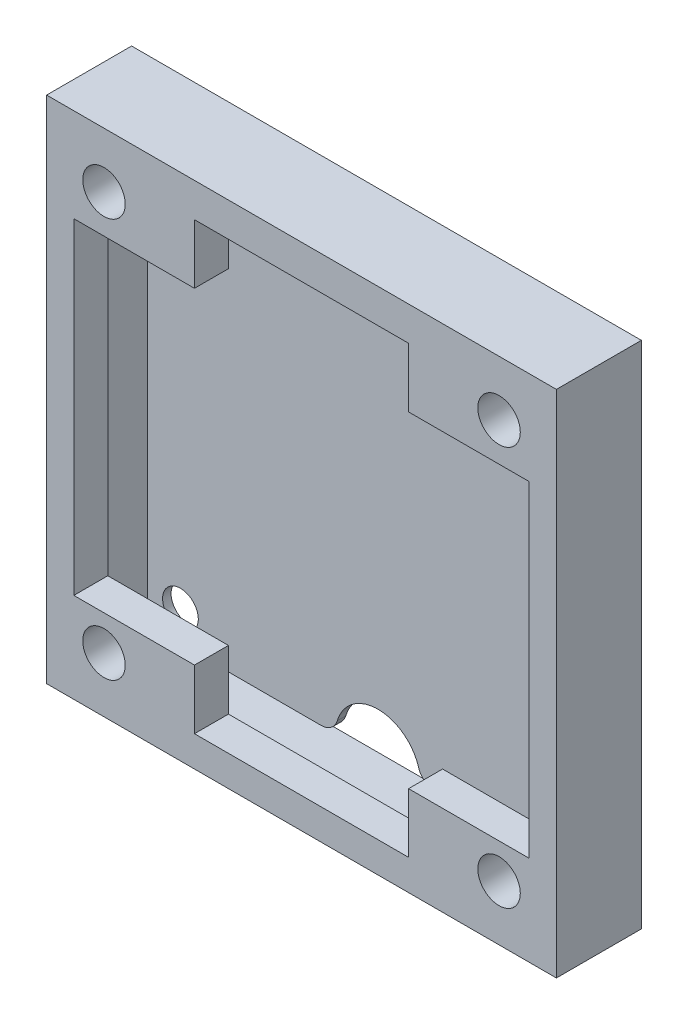
SolidWorks part; units mm, degrees
ref_plane "Front Plane" through (0, 0, 0) normal (0, 0, 1) x (1, 0, 0)
ref_plane "Top Plane" through (0, 0, 0) normal (0, 1, 0) x (1, 0, 0)
ref_plane "Right Plane" through (0, 0, 0) normal (1, 0, 0) x (0, 0, -1)
sketch "Sketch1" plane through (0, 0, 0) normal (0, 0, 1) x (1, 0, 0)
  line L0 (0, 0) -> (0, -0.1) construction
  line L1 (15, -15) -> (-15, -15)
  line L2 (15, -15) -> (15, 15)
  line L3 (15, 15) -> (-15, 15)
  line L4 (-15, -15) -> (-15, 15)
  line L5 (15, -15) -> (-15, 15) construction
  line L6 (15, 15) -> (-15, -15) construction
  line L7 (11.625, -11.75) -> (-11.625, -11.75) construction
  line L8 (11.625, -11.75) -> (11.625, 11.75) construction
  line L9 (11.625, 11.75) -> (-11.625, 11.75) construction
  line L10 (-11.625, -11.75) -> (-11.625, 11.75) construction
  line L11 (11.625, -11.75) -> (-11.625, 11.75) construction
  line L12 (11.625, 11.75) -> (-11.625, -11.75) construction
  line L13 (13.4, -9.7) -> (-13.4, -9.7)
  line L14 (13.4, -9.7) -> (13.4, 9.5)
  line L15 (13.4, 9.5) -> (-13.4, 9.5)
  line L16 (-13.4, -9.7) -> (-13.4, 9.5)
  line L17 (13.4, -9.7) -> (-13.4, 9.5) construction
  line L18 (13.4, 9.5) -> (-13.4, -9.7) construction
  circle A0 centre (-11.625, 11.75) radius 1.25
  circle A1 centre (11.625, 11.75) radius 1.25
  circle A2 centre (11.625, -11.75) radius 1.25
  circle A3 centre (-11.625, -11.75) radius 1.25
  point P0 (0, 0)
  point P6 (0, 0)
  point P15 (0, -0.1)
  point P22 (0, 6.9609)
  point P23 (0, 3.0514)
  dimension "D3" = 2.5
  dimension "D1" = 30
  dimension "D2" = 30
  dimension "D4" = 23.5
  dimension "D5" = 23.25
  dimension "D6" = 19.2
  dimension "D7" = 26.8
  dimension "D8" = 2.25
extrude "Boss-Extrude1" add sketch "Sketch1" along normal blind 2
sketch "Sketch2" plane through (0, 0, 2) normal (0, 0, 1) x (1, 0, 0)
  line L0 (-13.4, -9.7) -> (13.4, -9.7) construction
  line L1 (-6.3, -9.7) -> (6.3, -9.7)
  line L2 (-6.3, -9.7) -> (-6.3, -13.2)
  line L3 (-6.3, -13.2) -> (6.3, -13.2)
  line L4 (6.3, -9.7) -> (6.3, -13.2)
  line L5 (0, 0) -> (0, -9.7) construction
  line L6 (13.4, 9.5) -> (-13.4, 9.5) construction
  line L7 (-6.3, 9.5) -> (6.3, 9.5)
  line L8 (-6.3, 9.5) -> (-6.3, 13)
  line L9 (-6.3, 13) -> (6.3, 13)
  line L10 (6.3, 9.5) -> (6.3, 13)
  line L11 (0, 9.5) -> (0, 0) construction
  dimension "D1" = 12.6
  dimension "D2" = 3.5
  dimension "D3" = 12.6
  dimension "D4" = 3.5
extrude "Cut-Extrude1" cut sketch "Sketch2" against normal blind 3
sketch "Sketch3" plane through (0, 0, 0) normal (0, 0, -1) x (-1, 0, 0)
  line L8 (13.75, -13.75) -> (13.75, 13.75)
  line L9 (13.75, 13.75) -> (-13.75, 13.75)
  line L10 (-13.75, 13.75) -> (-13.75, -13.75)
  line L11 (-13.75, -13.75) -> (13.75, -13.75)
  line L12 (13.75, -13.75) -> (13.75, 13.75)
  line L13 (13.75, 13.75) -> (-13.75, 13.75)
  line L14 (-13.75, 13.75) -> (-13.75, -13.75)
  line L15 (-13.75, -13.75) -> (13.75, -13.75)
  line L16 (15, -15) -> (15, 15)
  line L17 (15, 15) -> (-15, 15)
  line L18 (-15, 15) -> (-15, -15)
  line L19 (-15, -15) -> (15, -15)
  line L20 (15, -15) -> (15, 15)
  line L21 (15, 15) -> (-15, 15)
  line L22 (-15, 15) -> (-15, -15)
  line L23 (-15, -15) -> (15, -15)
  dimension "D1" = 1.25
  dimension "D2" = 0
extrude "Boss-Extrude3" add sketch "Sketch3" along normal blind 3
sketch "Sketch4" plane through (0, 0, -3) normal (0, 0, -1) x (-1, 0, 0)
  line L4 (2.5, -13.55) -> (13.55, -13.55)
  line L8 (-13.55, 13.55) -> (-13.55, -13.55)
  line L9 (-13.55, -13.55) -> (13.55, -13.55)
  line L10 (13.55, -13.55) -> (13.55, 13.55)
  line L11 (13.55, 13.55) -> (-13.55, 13.55)
  line L12 (-13.55, 13.55) -> (-13.55, -13.55)
  line L13 (-13.55, -13.55) -> (-2.5, -13.55)
  line L14 (13.55, -13.55) -> (13.55, 13.55)
  line L15 (13.55, 13.55) -> (-13.55, 13.55)
  circle A28 centre (-11.625, 11.75) radius 1.05
  circle A29 centre (-11.625, 11.75) radius 1.05
  circle A31 centre (11.625, 11.75) radius 1.05
  circle A32 centre (11.625, 11.75) radius 1.05
  circle A34 centre (-11.625, -11.75) radius 1.05
  circle A35 centre (-11.625, -11.75) radius 1.05
  arc A36 (2.5, -13.55) -> (-2.5, -13.55) centre (0, -13.55) ccw
  circle A37 centre (11.625, -11.75) radius 1.05
  circle A38 centre (11.625, -11.75) radius 1.05
  point P1 (0, -13.8458)
  point P17 (0, 0)
  dimension "D6" = 5
  dimension "D1" = 0.2
  dimension "D2" = 0.2
  dimension "D3" = 0.2
  dimension "D4" = 0.2
  dimension "D5" = 0.2
extrude "Boss-Extrude4" add sketch "Sketch4" against normal blind 0.5 separate body
fillet "Fillet1" radius 1 2 edges at (2.5, -13.55, -2.75) (-2.5, -13.55, -2.75)
